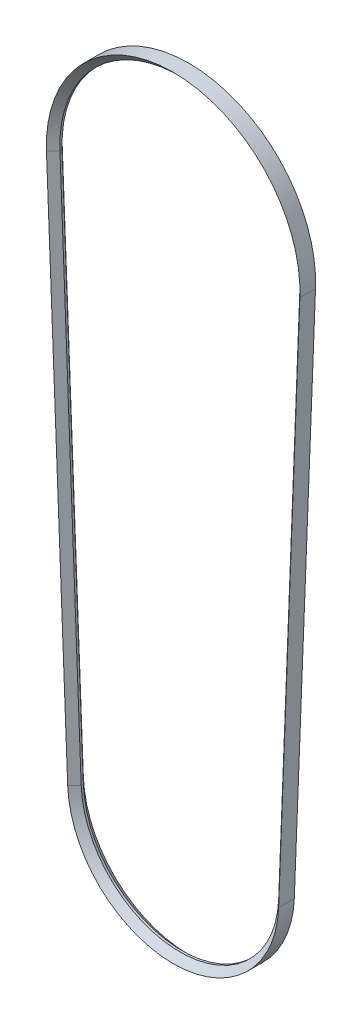
SolidWorks part; units mm, degrees
ref_plane "Front" through (0, 0, 0) normal (0, 0, 1) x (1, 0, 0)
ref_plane "Top" through (0, 0, 0) normal (0, 1, 0) x (1, 0, 0)
ref_plane "Right" through (0, 0, 0) normal (1, 0, 0) x (0, 0, -1)
sketch "Sketch1" plane through (0, 0, 0) normal (0, 0, 1) x (1, 0, 0)
  line L0 (139.8915, 629.4882) -> (114.9108, -4.5276)
  line L1 (-114.9108, -4.5276) -> (-139.8915, 629.4882)
  circle A0 centre (0, 0) radius 115 construction
  circle A1 centre (0, 635) radius 140 construction
  arc A2 (-114.9108, -4.5276) -> (114.9108, -4.5276) centre (0, 0) ccw
  arc A3 (139.8915, 629.4882) -> (-139.8915, 629.4882) centre (0, 635) ccw
ref_plane "Plane1" through (139.8915, 629.4882, 0) normal (-0.0394, -0.9992, 0) x (0.9992, -0.0394, 0)
sketch "Sketch2" plane through (139.8915, 629.4882, 0) normal (-0.0394, -0.9992, 0) x (0.9992, -0.0394, 0)
  line L0 (0, 0) -> (92.2165, 0) construction
  line L1 (0, 0) -> (10, 10) construction
  line L2 (10, -10) -> (0, 0) construction
  line L3 (1.2688, 1.2688) -> (9.2063, 9.2063)
  line L4 (9.2063, -9.2063) -> (1.2688, -1.2688)
  line L5 (9.2063, 9.2063) -> (9.2063, -9.2063)
  line L6 (10, 10) -> (10, 15) construction
  line L7 (1.2688, 1.2688) -> (1.2688, -1.2688)
  dimension "D1" = 0.7937
  dimension "D2" = 7.9375
sweep "Sweep1" add profiles "Sketch2" path "Sketch1"
